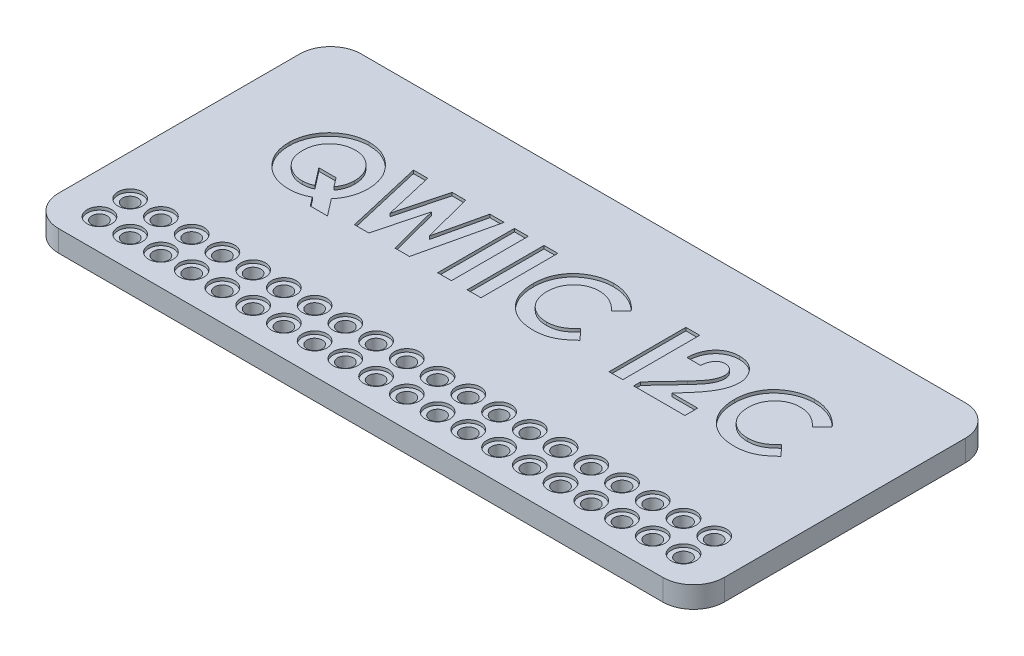
SolidWorks part; units mm, degrees
ref_plane "Front Plane" through (0, 0, 0) normal (0, 0, 1) x (1, 0, 0)
ref_plane "Top Plane" through (0, 0, 0) normal (0, 1, 0) x (1, 0, 0)
ref_plane "Right Plane" through (0, 0, 0) normal (1, 0, 0) x (0, 0, -1)
sketch "Sketch1" plane through (0, 0, 0) normal (0, 1, 0) x (1, 0, 0)
  line L1 (-27.5, -12.5) -> (27.5, -12.5)
  line L2 (-27.5, -12.5) -> (-27.5, 12.5)
  line L3 (-27.5, 12.5) -> (27.5, 12.5)
  line L4 (27.5, -12.5) -> (27.5, 12.5)
  line L5 (-27.5, -12.5) -> (27.5, 12.5) construction
  line L6 (-27.5, 12.5) -> (27.5, -12.5) construction
  point P0 (0, 0)
  dimension "D1" = 55
  dimension "D2" = 25
extrude "Boss-Extrude1" add sketch "Sketch1" along normal blind 1.7648 contours L2 L1 L4 L3
sketch "Sketch2" plane through (0, 1.7648, 0) normal (0, 1, 0) x (1, 0, 0)
  line L0 (-27.5, 0) -> (27.5, 0) construction
  line L1 (-27.5, -12.5) -> (-27.5, 12.5) construction
  line L2 (27.5, -12.5) -> (27.5, 12.5) construction
  text T0 "<b>QWIIC I2C</b>" font "Century Gothic" height in points 24
extrude "Cut-Extrude1" cut sketch "Sketch2" against normal blind 0.254
sketch "Sketch3" plane through (0, 1.7648, 0) normal (0, 1, 0) x (1, 0, 0)
  line L0 (-27.5, -9.96) -> (27.5, -9.96) construction
  line L1 (-27.5, -12.5) -> (-27.5, 12.5) construction
  line L2 (27.5, -12.5) -> (27.5, 12.5) construction
  line L3 (24.765, -7.42) -> (27.5, -7.42) construction
  line L4 (-24.765, -7.42) -> (-27.5, -7.42) construction
  line L5 (-27.5, -12.5) -> (27.5, -12.5) construction
  circle A0 centre (-24.13, -9.96) radius 0.635
  circle A2 centre (-21.59, -9.96) radius 0.635
  circle A3 centre (-19.05, -9.96) radius 0.635
  circle A4 centre (-16.51, -9.96) radius 0.635
  circle A5 centre (-13.97, -9.96) radius 0.635
  circle A6 centre (-11.43, -9.96) radius 0.635
  circle A7 centre (-8.89, -9.96) radius 0.635
  circle A8 centre (-6.35, -9.96) radius 0.635
  circle A9 centre (-3.81, -9.96) radius 0.635
  circle A10 centre (-1.27, -9.96) radius 0.635
  circle A11 centre (1.27, -9.96) radius 0.635
  circle A12 centre (3.81, -9.96) radius 0.635
  circle A13 centre (6.35, -9.96) radius 0.635
  circle A14 centre (8.89, -9.96) radius 0.635
  circle A15 centre (11.43, -9.96) radius 0.635
  circle A16 centre (13.97, -9.96) radius 0.635
  circle A17 centre (16.51, -9.96) radius 0.635
  circle A18 centre (19.05, -9.96) radius 0.635
  circle A19 centre (21.59, -9.96) radius 0.635
  circle A20 centre (24.13, -9.96) radius 0.635
  circle A21 centre (-21.59, -7.42) radius 0.635
  circle A22 centre (-19.05, -7.42) radius 0.635
  circle A23 centre (-16.51, -7.42) radius 0.635
  circle A24 centre (-13.97, -7.42) radius 0.635
  circle A25 centre (-11.43, -7.42) radius 0.635
  circle A26 centre (-8.89, -7.42) radius 0.635
  circle A27 centre (-6.35, -7.42) radius 0.635
  circle A28 centre (-3.81, -7.42) radius 0.635
  circle A29 centre (-1.27, -7.42) radius 0.635
  circle A30 centre (1.27, -7.42) radius 0.635
  circle A31 centre (3.81, -7.42) radius 0.635
  circle A32 centre (6.35, -7.42) radius 0.635
  circle A33 centre (8.89, -7.42) radius 0.635
  circle A34 centre (11.43, -7.42) radius 0.635
  circle A35 centre (13.97, -7.42) radius 0.635
  circle A36 centre (16.51, -7.42) radius 0.635
  circle A37 centre (19.05, -7.42) radius 0.635
  circle A38 centre (21.59, -7.42) radius 0.635
  circle A39 centre (24.13, -7.42) radius 0.635
  circle A40 centre (-24.13, -7.42) radius 0.635
  point P92 (-21.59, -9.96)
  point P93 (0, 0)
  dimension "D1" = 1.27
  dimension "D4" = 2.54
  dimension "D5" = 2.54
  dimension "D6" = 2.54
  dimension "D2" = 20
  dimension "D3" = 2
extrude "Cut-Extrude2" cut sketch "Sketch3" against normal through all
sketch "Sketch4" plane through (0, 1.7648, 0) normal (0, 1, 0) x (1, 0, 0)
  circle A0 centre (-24.13, -9.96) radius 0.635 construction
  circle A1 centre (-24.13, -9.96) radius 0.635 construction
  circle A2 centre (-24.13, -9.96) radius 1.016
  circle A3 centre (-21.59, -9.96) radius 1.016
  circle A4 centre (-19.05, -9.96) radius 1.016
  circle A5 centre (-16.51, -9.96) radius 1.016
  circle A6 centre (-13.97, -9.96) radius 1.016
  circle A7 centre (-11.43, -9.96) radius 1.016
  circle A8 centre (-8.89, -9.96) radius 1.016
  circle A9 centre (-6.35, -9.96) radius 1.016
  circle A10 centre (-3.81, -9.96) radius 1.016
  circle A11 centre (-1.27, -9.96) radius 1.016
  circle A12 centre (1.27, -9.96) radius 1.016
  circle A13 centre (3.81, -9.96) radius 1.016
  circle A14 centre (6.35, -9.96) radius 1.016
  circle A15 centre (8.89, -9.96) radius 1.016
  circle A16 centre (11.43, -9.96) radius 1.016
  circle A17 centre (13.97, -9.96) radius 1.016
  circle A18 centre (16.51, -9.96) radius 1.016
  circle A19 centre (19.05, -9.96) radius 1.016
  circle A20 centre (21.59, -9.96) radius 1.016
  circle A21 centre (24.13, -9.96) radius 1.016
  circle A22 centre (-21.59, -7.42) radius 1.016
  circle A23 centre (-19.05, -7.42) radius 1.016
  circle A24 centre (-16.51, -7.42) radius 1.016
  circle A25 centre (-13.97, -7.42) radius 1.016
  circle A26 centre (-11.43, -7.42) radius 1.016
  circle A27 centre (-8.89, -7.42) radius 1.016
  circle A28 centre (-6.35, -7.42) radius 1.016
  circle A29 centre (-3.81, -7.42) radius 1.016
  circle A30 centre (-1.27, -7.42) radius 1.016
  circle A31 centre (1.27, -7.42) radius 1.016
  circle A32 centre (3.81, -7.42) radius 1.016
  circle A33 centre (6.35, -7.42) radius 1.016
  circle A34 centre (8.89, -7.42) radius 1.016
  circle A35 centre (11.43, -7.42) radius 1.016
  circle A36 centre (13.97, -7.42) radius 1.016
  circle A37 centre (16.51, -7.42) radius 1.016
  circle A38 centre (19.05, -7.42) radius 1.016
  circle A39 centre (21.59, -7.42) radius 1.016
  circle A40 centre (24.13, -7.42) radius 1.016
  circle A41 centre (-24.13, -7.42) radius 1.016
  point P4 (0, 0)
  dimension "D5" = 2.032
  dimension "D3" = 2.54
  dimension "D4" = 2.54
  dimension "D1" = 20
  dimension "D2" = 2
extrude "Cut-Extrude3" cut sketch "Sketch4" against normal blind 0.254
sketch "Sketch5" plane through (0, 0, 0) normal (0, -1, 0) x (1, 0, 0)
  line L0 (-27.5, -12.5) -> (27.5, -12.5) construction
  line L1 (19.3357, -8.182) -> (13.2397, -8.182)
  line L2 (19.3357, -8.182) -> (19.3357, -12.5)
  line L3 (19.3357, -12.5) -> (13.2398, -12.5)
  line L4 (13.2397, -8.182) -> (13.2398, -12.5)
  line L5 (19.3357, -8.182) -> (13.2398, -12.5) construction
  line L6 (19.3357, -12.5) -> (13.2397, -8.182) construction
  line L7 (15.7881, -10.341) -> (-49984.2119, -10.341) construction
  line L8 (8.4772, -8.182) -> (2.3812, -8.182)
  line L9 (8.4772, -8.182) -> (8.4772, -12.5)
  line L10 (8.4772, -12.5) -> (2.3812, -12.5)
  line L11 (2.3812, -8.182) -> (2.3812, -12.5)
  line L12 (8.4772, -8.182) -> (2.3812, -12.5) construction
  line L13 (8.4772, -12.5) -> (2.3812, -8.182) construction
  line L14 (-2.3813, -8.182) -> (-8.4773, -8.182)
  line L15 (-2.3813, -8.182) -> (-2.3813, -12.5)
  line L16 (-2.3813, -12.5) -> (-8.4773, -12.5)
  line L17 (-8.4773, -8.182) -> (-8.4773, -12.5)
  line L18 (-2.3813, -8.182) -> (-8.4773, -12.5) construction
  line L19 (-2.3813, -12.5) -> (-8.4773, -8.182) construction
  line L20 (-13.2398, -8.182) -> (-19.3358, -8.182)
  line L21 (-13.2398, -8.182) -> (-13.2398, -12.5)
  line L22 (-13.2398, -12.5) -> (-19.3358, -12.5)
  line L23 (-19.3358, -8.182) -> (-19.3358, -12.5)
  line L24 (-13.2398, -8.182) -> (-19.3358, -12.5) construction
  line L25 (-13.2398, -12.5) -> (-19.3358, -8.182) construction
  line L26 (19.3357, -8.182) -> (27.5, -8.182) construction
  line L27 (27.5, 12.5) -> (27.5, -12.5) construction
  line L28 (-19.3358, -8.182) -> (-27.5, -8.182) construction
  line L29 (-27.5, 12.5) -> (-27.5, -12.5) construction
  point P0 (16.2877, -10.341)
  point P9 (8.0405, -8.182)
  point P10 (5.4292, -10.341)
  point P15 (-5.4293, -10.341)
  point P20 (-16.2878, -10.341)
  point P31 (0, 0)
  dimension "D1" = 4.318
  dimension "D2" = 6.096
  dimension "D4" = 4.7625
  dimension "D3" = 4
extrude "Boss-Extrude2" add sketch "Sketch5" along normal blind 4.318
fillet "Fillet1" radius 2.54 4 edges at (27.5, 0.8824, 12.5) (27.5, 0.8824, -12.5) (-27.5, 0.8824, 12.5) (-27.5, 0.8824, -12.5)
